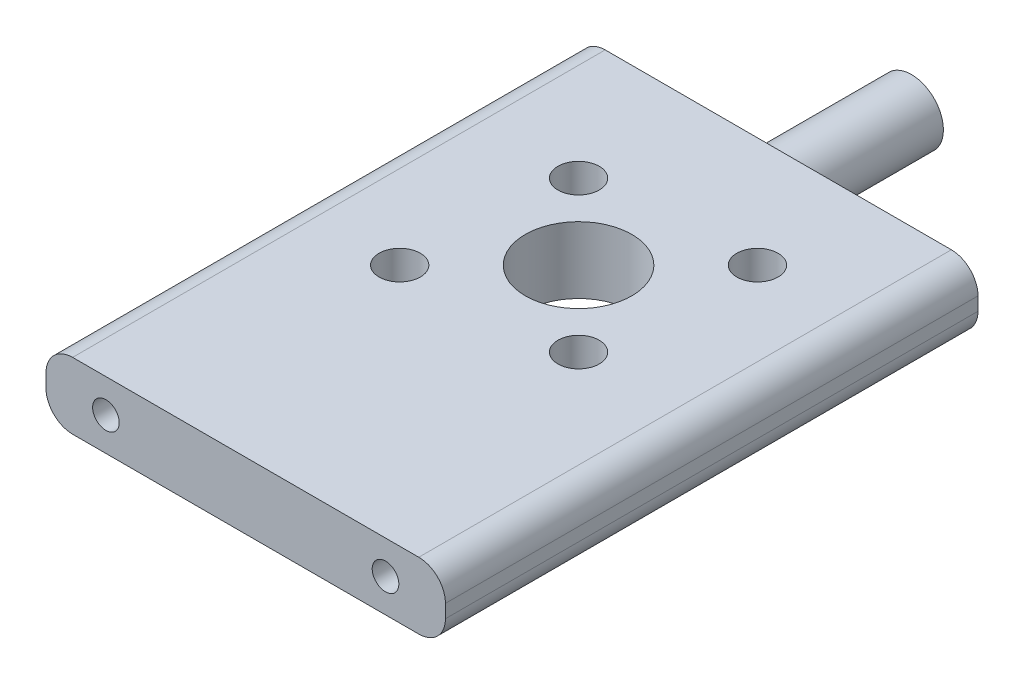
SolidWorks part; units mm, degrees
ref_plane "Front Plane" through (0, 0, 0) normal (0, 0, 1) x (1, 0, 0)
ref_plane "Top Plane" through (0, 0, 0) normal (0, 1, 0) x (1, 0, 0)
ref_plane "Right Plane" through (0, 0, 0) normal (1, 0, 0) x (0, 0, -1)
sketch "Sketch1" plane through (0, 0, 0) normal (0, 1, 0) x (1, 0, 0)
  line L1 (22.6874, -13.8055) -> (-7.3126, -13.8055)
  line L2 (22.6874, -13.8055) -> (22.6874, 26.1945)
  line L3 (22.6874, 26.1945) -> (-7.3126, 26.1945)
  line L4 (-7.3126, -13.8055) -> (-7.3126, 26.1945)
  dimension "D1" = 30
  dimension "D2" = 40
extrude "Boss-Extrude1" add sketch "Sketch1" along normal blind 5
sketch "Sketch2" plane through (0, 5, 0) normal (0, 1, 0) x (-1, 0, 0)
  line L0 (-22.6874, -26.1945) -> (7.3126, -26.1945) construction
  line L1 (-22.6874, 13.8055) -> (-22.6874, -26.1945) construction
  circle A0 centre (-7.6874, -11.1945) radius 4
  dimension "D1" = 8
  dimension "D2" = 15
  dimension "D3" = 15
extrude "Cut-Extrude1" cut sketch "Sketch2" against normal blind 5
sketch "Sketch3" plane through (0, 5, 0) normal (0, 1, 0) x (1, 0, 0)
  line L0 (22.6874, -13.8055) -> (22.6874, 26.1945) construction
  line L1 (22.6874, 26.1945) -> (-7.3126, 26.1945) construction
  circle A0 centre (2.0306, 16.8513) radius 1.55
  circle A1 centre (14.4049, 17.912) radius 1.55
  circle A2 centre (13.3443, 5.5376) radius 1.55
  circle A3 centre (0.9699, 4.477) radius 1.55
  point P8 (7.6874, 11.1945)
  dimension "D1" = 3.1
  dimension "D2" = 3.1
  dimension "D3" = 3.1
  dimension "D4" = 3.1
  dimension "D5" = 19
  dimension "D6" = 16
  dimension "D7" = 9.5
  dimension "D8" = 8
  dimension "D9" = 15
  dimension "D10" = 15
extrude "Cut-Extrude2" cut sketch "Sketch3" against normal blind 5
sketch "Sketch4" plane through (0, 0, 13.8055) normal (0, 0, 1) x (1, 0, 0)
  line L0 (-7.3126, 5) -> (22.6874, 5) construction
  line L1 (-7.3126, 5) -> (-7.3126, 0) construction
  circle A0 centre (-2.8126, 2.5) radius 1
  circle A1 centre (18.1874, 2.5) radius 1
  dimension "D1" = 2
  dimension "D2" = 2
  dimension "D3" = 2.5
  dimension "D4" = 2.5
  dimension "D5" = 21
  dimension "D6" = 4.5
extrude "Cut-Extrude3" cut sketch "Sketch4" against normal blind 5
sketch "Sketch5" plane through (0, 0, -26.1945) normal (0, 0, -1) x (-1, 0, 0)
  line L0 (-22.6874, 0) -> (7.3126, 0) construction
  line L1 (-22.6874, 5) -> (-22.6874, 0) construction
  circle A0 centre (-7.6874, 2.5) radius 2.4
  dimension "D1" = 4.8
  dimension "D2" = 2.5
  dimension "D3" = 15
extrude "Boss-Extrude2" add sketch "Sketch5" along normal blind 10
fillet "Fillet1" radius 2 4 edges at (22.6874, 0, -6.1945) (-7.3126, 0, -6.1945) (22.6874, 5, -6.1945) (-7.3126, 5, -6.1945)
